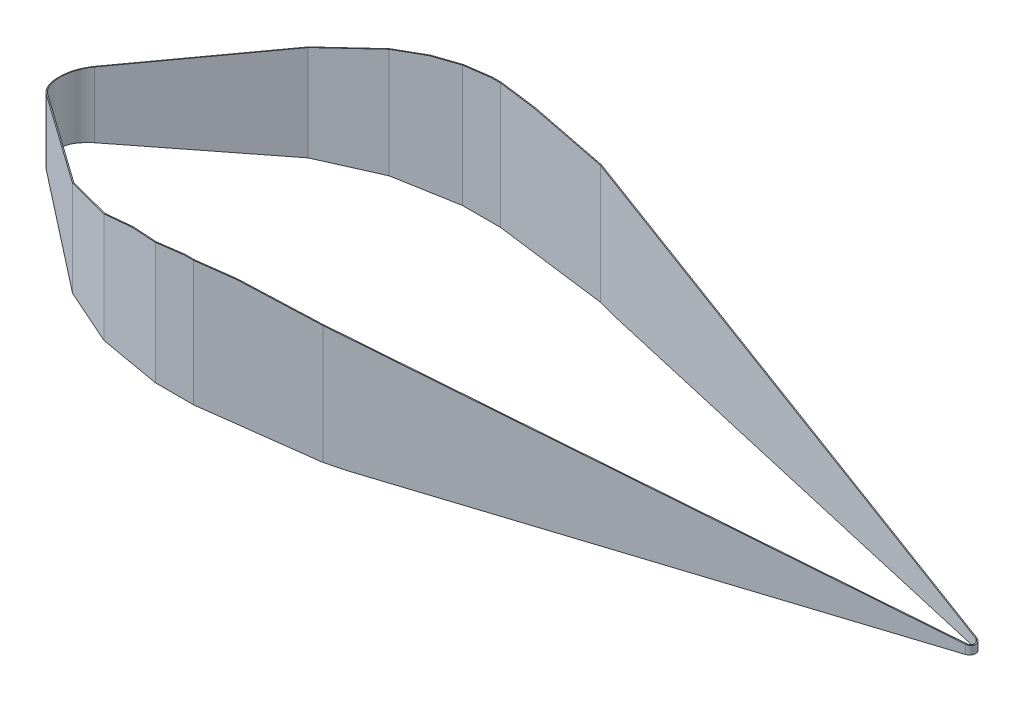
SolidWorks part; units mm, degrees
ref_plane "Front Plane" through (0, 0, 0) normal (0, 0, 1) x (1, 0, 0)
ref_plane "Top Plane" through (0, 0, 0) normal (0, 1, 0) x (1, 0, 0)
ref_plane "Right Plane" through (0, 0, 0) normal (1, 0, 0) x (0, 0, -1)
sketch "Sketch1" plane through (0, 0, 0) normal (0, 1, 0) x (1, 0, 0)
  line L0 (161.4098, 126.0887) -> (784.13, 612.54)
  line L1 (784.13, 612.54) -> (1076.464, 742.696)
  line L2 (1076.464, 742.696) -> (1401.451, 800)
  line L3 (1401.451, 800) -> (1600, 800)
  line L4 (1600, 800) -> (2195.064, 723.196)
  line L5 (2195.064, 723.196) -> (4839.4634, 29.0169)
  line L6 (4839.4634, -29.0169) -> (2195.064, -723.196)
  line L7 (2195.064, -723.196) -> (1600, -800)
  line L8 (1600, -800) -> (1401.451, -800)
  line L9 (1401.451, -800) -> (1076.464, -742.696)
  line L10 (1076.464, -742.696) -> (784.13, -612.54)
  line L11 (784.13, -612.54) -> (161.4098, -126.0887)
  arc A0 (161.4098, 126.0887) -> (161.4098, -126.0887) centre (259.9067, 0) ccw
  arc A1 (4839.4634, 29.0169) -> (4839.4634, -29.0169) centre (4831.8462, 0) cw
  point P15 (0, 0)
  point P18 (4950, 0)
  dimension "r0" = 160
  dimension "r6" = 30
  dimension "x1" = 784.13
  dimension "x2" = 1076.464
  dimension "x3" = 1401.451
  dimension "x4" = 1600
  dimension "x5" = 2195.064
  dimension "x6" = 4950
  dimension "x7" = 2195.064
  dimension "x8" = 1600
  dimension "x9" = 1401.451
  dimension "x10" = 1076.464
  dimension "x11" = 784.13
  dimension "y1" = 612.54
  dimension "y2" = 742.696
  dimension "y3" = 800
  dimension "y5" = 723.196
  dimension "y7" = 723.196
  dimension "y8" = 800
  dimension "y10" = 742.696
  dimension "y11" = 612.54
extrude "TopView_Extrude" add sketch "Sketch1" along normal blind 800
shell "Shell1" thickness 5
sketch "Sketch2" plane through (0, 0, 0) normal (0, 0, 1) x (1, 0, 0)
  line L0 (0, 300) -> (0, 332.8541)
  line L1 (113.6551, 478.3843) -> (1255.921, 763.655)
  line L2 (1255.921, 763.655) -> (1551.451, 800)
  line L3 (1551.451, 800) -> (1800, 800)
  line L4 (1800, 800) -> (2197.056, 765.81)
  line L5 (2197.056, 765.81) -> (4950, 288.165)
  line L6 (4950, 288.165) -> (4950, 265.638)
  line L7 (4950, 265.638) -> (2301.451, 150)
  line L8 (2301.451, 150) -> (150, 150)
  arc A0 (0, 300) -> (150, 150) centre (150, 300) ccw
  arc A1 (0, 332.8541) -> (113.6551, 478.3843) centre (150, 332.8541) cw
  point P12 (0, 150)
  point P15 (0, 450)
  dimension "r0" = 150
  dimension "r1" = 150
  dimension "x2" = 1255.921
  dimension "x3" = 1551.451
  dimension "x4" = 1800
  dimension "x5" = 2197.056
  dimension "x6" = 4950
  dimension "x8" = 2301.451
  dimension "y0" = 150
  dimension "y1" = 450
  dimension "y2" = 763.655
  dimension "y3" = 800
  dimension "y5" = 765.81
  dimension "y6" = 288.165
  dimension "y7" = 265.638
extrude "SideProfile_Cut" cut sketch "Sketch2" against normal through all and the other way through all flip side to cut
